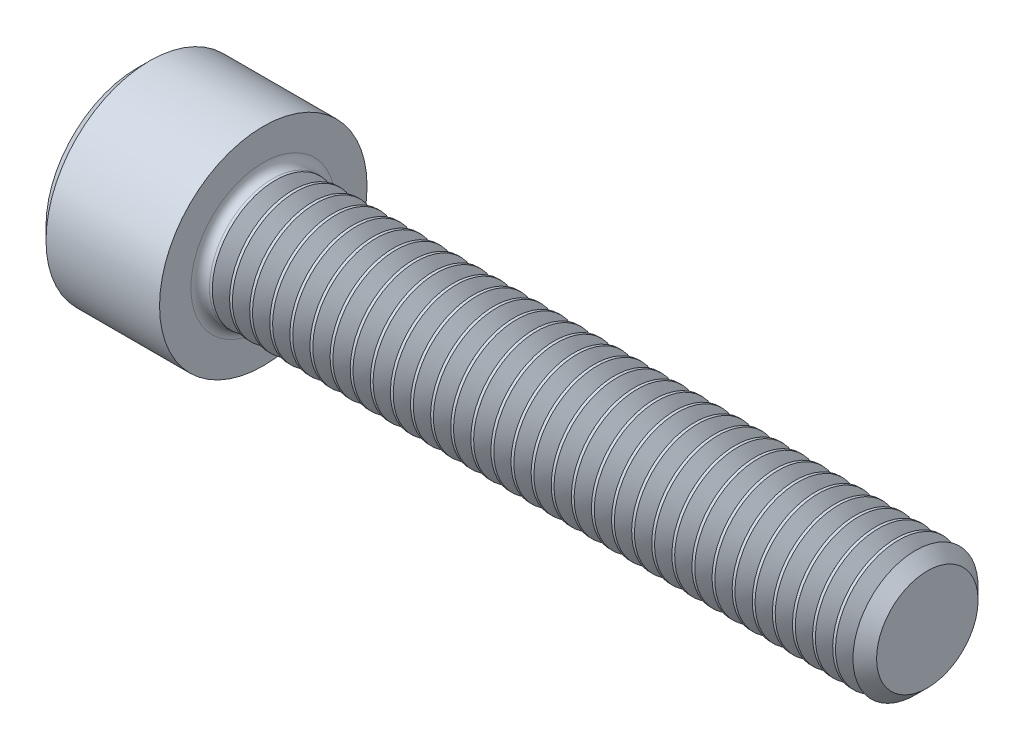
SolidWorks part; units mm, degrees
revolve "Base-Revolve" add sketch "BodySke"
sketch "BodySke" plane through (0, 0, 0) normal (0, 0, 1) x (1, 0, 0)
  line L0 (0, 0) -> (0, 3.4862)
  line L1 (0.4826, 3.9688) -> (4.826, 3.9688)
  line L2 (4.826, 3.9688) -> (4.826, 2.413)
  line L3 (4.826, 2.413) -> (29.7536, 2.413)
  line L4 (30.226, 1.9406) -> (30.226, 0)
  line L5 (30.226, 0) -> (0, 0)
  line L6 (-31.75, 0) -> (127, 0) construction
  line L7 (0, 3.4862) -> (0.4826, 3.9688)
  line L8 (30.226, 1.9406) -> (29.7536, 2.413)
  line L9 (0, -3.4862) -> (0.4826, -3.9688) construction
  line L10 (30.226, -1.9406) -> (29.7536, -2.413) construction
  line L11 (5.6185, 9.525) -> (5.6185, 3.175) construction
  line L12 (4.826, 9.525) -> (4.826, 3.175) construction
  line L13 (-7.874, 9.525) -> (-7.874, 3.175) construction
  dimension "Diameter" = 4.826
  dimension "Head_ht" = 4.826
  dimension "Length" = 25.4
  dimension "Body_ch_ang" = 45
  dimension "Head_dia" = 7.9375
  dimension "Head_ch_ang" = 45
  dimension "Head_side_ht" = 4.3434
  dimension "Minor_dia" = 3.8811
  dimension "Advance" = 0.7925
  dimension "Thread_nom" = 25.4
  dimension "Thread_length" = 38.1
cosmetic thread "ThreadCosmetic" [suppressed]
fillet "Fillet1" radius 0.3556 1 edges at (4.826, 0, 2.413)
ref_plane "Plane1" through (0, 0, 0) normal (0, 0, 1) x (1, 0, 0)
ref_plane "Plane2" through (0, 0, 0) normal (0, 1, 0) x (1, 0, 0)
ref_plane "Plane3" through (0, 0, 0) normal (1, 0, 0) x (0, 0, -1)
other "Configuration Table"
sketch "Sketch2" plane through (0, 0, 0) normal (0, 0, 1) x (1, 0, 0)
  line L0 (0, 1.985) -> (2.286, 1.985)
  line L1 (2.286, 1.985) -> (3.432, 0)
  line L2 (-31.75, 0) -> (127, 0) construction
  line L3 (3.432, 0) -> (0, 0)
  line L4 (0, 0) -> (0, 1.985)
  line L5 (0, 3.4862) -> (0, -3.4862) construction
  line L6 (0, 0) -> (47.625, 0) construction
  line L7 (4.826, -3.9688) -> (4.826, 3.9688) construction
  dimension "D1" = 1.985
  dimension "D2" = 60
revolve "Hex-PreBroach" cut sketch "Sketch2" angle 360 about L6
sketch "Sketch3" plane through (0, 0, 0) normal (-1, 0, 0) x (0, 0.5, 0.866)
  line L0 (1.146, 1.985) -> (-1.146, 1.985)
  line L1 (-1.146, 1.985) -> (-2.2921, 0)
  line L2 (1.146, 1.985) -> (2.2921, 0)
  line L3 (1.146, -1.985) -> (2.2921, 0)
  line L4 (1.146, -1.985) -> (-1.146, -1.985)
  line L5 (-1.146, -1.985) -> (-2.2921, 0)
  dimension "D1" = 1.985
  dimension "D2" = 1.985
  dimension "Hex_size" = 3.97
extrude "Hex" cut sketch "Sketch3" against normal blind 2.286
sketch "Sketch4" plane through (0, 0, 0) normal (-1, 0, 0) x (0, 0, 1)
  line L0 (0, 0) -> (2.3876, 0)
  line L1 (0, 0) -> (6.1484, 3.5498) construction
  line L2 (0, 0) -> (1.1938, 2.0677)
  line L3 (1.9883, 0.576) -> (2.2704, 0.7389)
  line L4 (1.493, 1.4339) -> (1.7751, 1.5968)
  arc A0 (1.9883, 0.576) -> (1.493, 1.4339) centre (0, 0) ccw
  arc A1 (2.3876, 0) -> (2.2704, 0.7389) centre (0, 0) ccw
  arc A2 (1.1938, 2.0677) -> (1.7751, 1.5968) centre (0, 0) cw
  dimension "D1" = 30
  dimension "D2" = 60
  dimension "Spline_p_dim" = 0.9906
  dimension "D3" = 0.4953
extrude "Spline" [suppressed] cut sketch "Sketch4" against normal blind 2.286
pattern_circular "CirPattern1" [suppressed] count 6 every 60
sketch "Sketch5" plane through (0, 0, 0) normal (0, 0, 1) x (1, 0, 0)
  line L0 (-31.75, 0) -> (127, 0) construction
  line L2 (0, 3.4862) -> (0, -3.4862) construction
  circle A0 centre (1.651, 0) radius 0.5905
  dimension "Drilled_hole_dia" = 1.1811
  dimension "Drilled_hole_loc" = 1.651
extrude "Hole" [suppressed] cut sketch "Sketch5" against normal through all and the other way through all
pattern_circular "Drilled-4" [suppressed] count 2 every 60
pattern_circular "Drilled-6" [suppressed] count 3 every 60
sketch "ThdSchSke" plane through (0, 0, 0) normal (0, 0, 1) x (1, 0, 0)
  line L0 (5.6185, -1.9406) -> (5.2877, -2.413)
  line L1 (5.6185, -1.9406) -> (5.9493, -2.413)
  line L2 (5.9493, -2.413) -> (5.9493, -3.0162)
  line L3 (-3.175, 0) -> (5.1513, 0) construction
  line L5 (5.9493, -3.0162) -> (5.2877, -3.0162)
  line L6 (5.2877, -3.0162) -> (5.2877, -2.413)
  line L7 (0, 3.4862) -> (0, -3.4862) construction
  dimension "Thread_minor" = 3.8811
  dimension "Diameter" = 4.826
  dimension "Start" = 5.6185
revolve "ThreadSchematic" cut sketch "ThdSchSke" angle 360 about L3
pattern_linear "ThdSchPat" count 32 spacing 0.769 along (1, 0, 0) of "ThreadSchematic"
equation "\"D2@Sketch3\" = \"Hex_size@Sketch3\" / 2"
equation "\"D1@Sketch3\" = \"Hex_size@Sketch3\" / 2"
equation "\"D1@Sketch2\" = \"Hex_size@Sketch3\" / 2"
equation "\"D3@Sketch4\" = \"Spline_p_dim@Sketch4\" / 2"
equation "\"Thread_minor@ThreadCosmetic\"  =  \"Minor_dia@BodySke\""
equation "\"D2@CirPattern1\" = 360 / \"Num_teeth@CirPattern1\""
equation "\"Wall_thickness@Sketch2\" = \"Head_ht@BodySke\" - \"Key_eng@Hex\""
equation "\"Thread_length@ThreadCosmetic\" = ((sgn( (\"Length@BodySke\" - \"Advance@BodySke\" ) - \"Thread_nom@BodySke\" )-1)*( (\"Length@BodySke\" - \"Advance@BodySke\" ) - \"Thread_nom@BodySke\" ))/-2+ \"Thread_nom@BodySke\""
equation "\"Thread_minor@ThdSchSke\" = \"Minor_dia@BodySke\""
equation "\"Diameter@ThdSchSke\" = \"Diameter@BodySke\""
equation "\"Overcut@ThdSchSke\" = \"Diameter@BodySke\" * 1.25"
equation "\"Start@ThdSchSke\" = \"Head_ht@BodySke\" + \"Length@BodySke\" - \"Thread_length@ThreadCosmetic\"  '---Non-countersunk---"
equation "\"Num_threads@ThdSchPat\" = int( \"Thread_length@ThreadCosmetic\" / \"Advance@BodySke\" + 0.999 )  + 1"
equation "\"Advance@ThdSchPat\" = \"Thread_length@ThreadCosmetic\" /  (\"Num_threads@ThdSchPat\" - 1) 'relax it"
equation "\"Num_threads@ThdSchPat\" = \"Num_threads@ThdSchPat\" - sgn( \"Num_threads@ThdSchPat\" - 1) '---chamfered tips only---"
